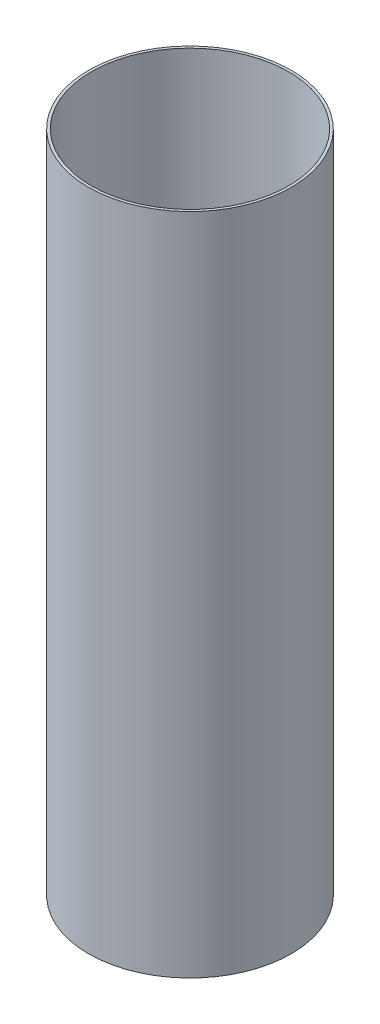
SolidWorks part; units mm, degrees
material "S-Glass Fiber"
ref_plane "Front Plane" through (0, 0, 0) normal (0, 0, 1) x (1, 0, 0)
ref_plane "Top Plane" through (0, 0, 0) normal (0, 1, 0) x (1, 0, 0)
ref_plane "Right Plane" through (0, 0, 0) normal (1, 0, 0) x (0, 0, -1)
sketch "Sketch1" plane through (0, 0, 0) normal (0, 1, 0) x (1, 0, 0)
  circle A0 centre (0, 0) radius 76.2
  circle A1 centre (0, 0) radius 78.2
  dimension "D1" = 2
  dimension "D2" = 152.4
extrude "Boss-Extrude1" add sketch "Sketch1" along normal blind 512
